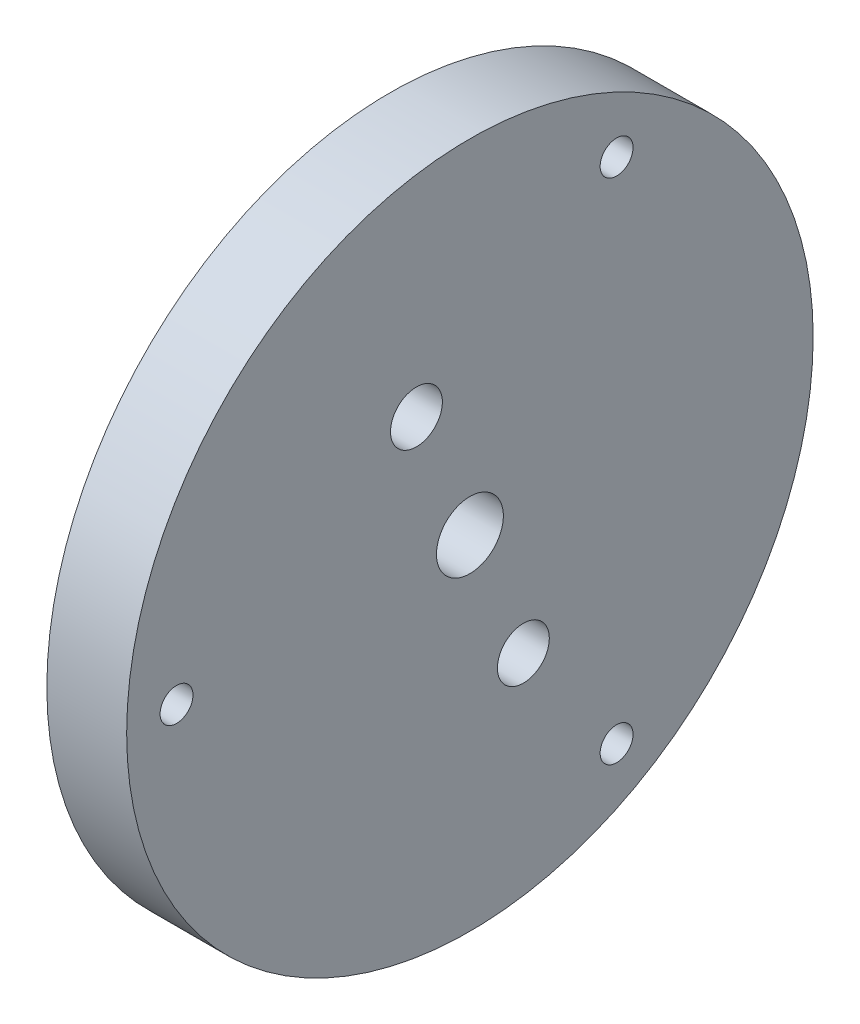
SolidWorks part; units mm, degrees
ref_plane "Front Plane" through (0, 0, 0) normal (0, 0, 1) x (1, 0, 0)
ref_plane "Top Plane" through (0, 0, 0) normal (0, 1, 0) x (1, 0, 0)
ref_plane "Right Plane" through (0, 0, 0) normal (1, 0, 0) x (0, 0, -1)
sketch "Axial profile (mm)" plane through (0, 0, 0) normal (0, 0, 1) x (1, 0, 0)
  line L0 (-110, 0) -> (75, 0) construction
  line L1 (148.7, 3.35) -> (156.7, 3.35)
  line L2 (156.7, 3.35) -> (156.7, 34.4)
  line L3 (156.7, 34.4) -> (148.7, 34.4)
  line L4 (148.7, 34.4) -> (148.7, 3.35)
revolve "Full revolution" add sketch "Axial profile (mm)" angle 360 about L0
sketch "Sketch2" plane through (0, 0, 0) normal (1, 0, 0) x (0, 0, -1)
  circle A0 centre (-5.3576, 12.9343) radius 2.6
  circle A1 centre (5.3576, -12.9343) radius 2.6
  circle A2 centre (-29.4, 0) radius 1.65
  circle A3 centre (14.7, -25.4611) radius 1.65
  circle A4 centre (14.7, 25.4611) radius 1.65
extrude "Axial holes" cut sketch "Sketch2" against normal through all and the other way through all
